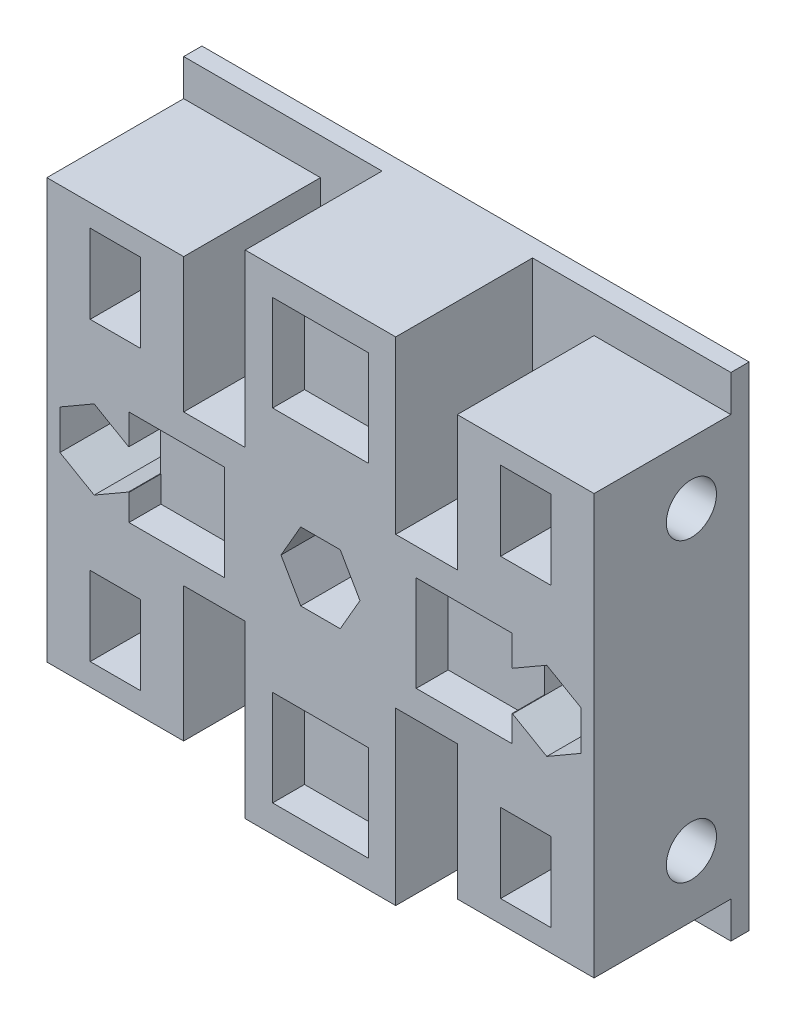
SolidWorks part; units mm, degrees
ref_plane "Plan de face" through (0, 0, 0) normal (0, 0, 1) x (1, 0, 0)
ref_plane "Plan de dessus" through (0, 0, 0) normal (0, 1, 0) x (1, 0, 0)
ref_plane "Plan de droite" through (0, 0, 0) normal (1, 0, 0) x (0, 0, -1)
sketch "Esquisse1" plane through (0, 0, 0) normal (0, 0, 1) x (1, 0, 0)
  line L1 (0, 0) -> (60, 0)
  line L2 (0, 0) -> (0, -54)
  line L3 (0, -54) -> (60, -54)
  line L4 (60, 0) -> (60, -54)
  circle A0 centre (5, -27) radius 2
  circle A1 centre (30, -27) radius 2
  circle A2 centre (55, -27) radius 2
  dimension "D1" = 4
  dimension "D2" = 4
  dimension "D3" = 4
  dimension "D4" = 25
  dimension "D5" = 25
  dimension "D6" = 60
  dimension "D7" = 54
  dimension "D8" = 27
  dimension "D9" = 5
  dimension "D10" = 27
  dimension "D11" = 27
extrude "Boss.-Extru.1" add sketch "Esquisse1" along normal blind 2
sketch "Esquisse2" plane through (0, 0, 2) normal (0, 0, 1) x (1, 0, 0)
  line L0 (0, 0) -> (0, -54) construction
  line L1 (0, -50) -> (15, -50)
  line L2 (15, -50) -> (15, -36.5)
  line L5 (0, -54) -> (60, -54) construction
  line L8 (15, -36.5) -> (0, -36.5)
  dimension "D1" = 4
  dimension "D2" = 15
  dimension "D4" = 13.5
extrude "Boss.-Extru.2" add sketch "Esquisse2" along normal blind 15
sketch "Esquisse4" plane through (0, 0, 0) normal (-1, 0, 0) x (0, 0, 1)
  line L1 (9.5, -45.4151) -> (9.5, -41.0849)
  line L2 (9.5, -41.0849) -> (5.75, -38.9199)
  line L3 (5.75, -38.9199) -> (2, -41.0849)
  line L4 (2, -41.0849) -> (2, -45.4151)
  line L5 (2, -45.4151) -> (5.75, -47.5801)
  line L6 (5.75, -47.5801) -> (9.5, -45.4151)
  line L7 (2, 0) -> (2, -36.5) construction
  line L8 (17, -36.5) -> (2, -36.5) construction
  circle A0 centre (5.75, -43.25) radius 3.75 construction
  dimension "D1" = 7.5
  dimension "D2" = 0
  dimension "D3" = 6.75
extrude "Enlèv. mat.-Extru.2" cut sketch "Esquisse4" against normal blind 16
sketch "Esquisse5" plane through (0, 0, 17) normal (0, 0, 1) x (1, 0, 0)
  line L0 (0, -50) -> (15, -50) construction
  line L1 (0, -36.5) -> (4.75, -36.5)
  line L2 (0, -36.5) -> (0, -50)
  line L3 (0, -50) -> (4.75, -50)
  line L4 (4.75, -36.5) -> (4.75, -50)
  line L5 (15, -36.5) -> (0, -36.5) construction
  line L6 (15, -50) -> (10.25, -50)
  line L7 (15, -50) -> (15, -36.5)
  line L8 (15, -36.5) -> (10.25, -36.5)
  line L9 (10.25, -50) -> (10.25, -36.5)
  dimension "D1" = 4.75
  dimension "D2" = 4.75
  dimension "D3" = 5.5
extrude "Boss.-Extru.3" add sketch "Esquisse5" against normal blind 17
sketch "Esquisse6" plane through (0, 0, 17) normal (0, 0, 1) x (1, 0, 0)
  line L0 (15, -36.5) -> (0, -36.5) construction
  line L1 (4.75, -36.5) -> (10.25, -36.5)
  line L2 (4.75, -36.5) -> (4.75, -50)
  line L3 (4.75, -50) -> (10.25, -50)
  line L4 (10.25, -36.5) -> (10.25, -50)
  line L5 (0, -50) -> (15, -50) construction
  line L6 (0, -36.5) -> (0, -50) construction
  line L7 (15, -50) -> (15, -36.5) construction
  line L9 (4.75, -38.92) -> (10.25, -38.92)
  line L10 (4.75, -38.92) -> (4.75, -47.58)
  line L11 (4.75, -47.58) -> (10.25, -47.58)
  line L12 (10.25, -38.92) -> (10.25, -47.58)
  dimension "D1" = 5.5
  dimension "D2" = 4.75
  dimension "D3" = 4.75
  dimension "D4" = 8.66
  dimension "D5" = 2.42
  dimension "D6" = 2.42
  dimension "D7" = 13.5
extrude "Enlèv. mat.-Extru.3" cut sketch "Esquisse6" against normal blind 11.25 contours L2 L11 L4 L9
sketch "Esquisse7" plane through (0, 0, 0) normal (-1, 0, 0) x (0, 0, 1)
  line L2 (17, -50) -> (2, -50) construction
  line L3 (2, -50) -> (2, -54) construction
  circle A0 centre (6.33, -43.25) radius 2.75
  dimension "D2" = 5.5
  dimension "D1" = 4.33
  dimension "D3" = 6.75
extrude "Enlèv. mat.-Extru.4" cut sketch "Esquisse7" against normal blind 28
ref_plane "Plan2" through (0, -27, 0) normal (0, -1, 0) x (-1, 0, 0)
ref_plane "Plan3" through (30, 0, 0) normal (-1, 0, 0) x (0, 0, 1)
mirror "Symétrie1" about plane through (0, -27, 0) normal (0, -1, 0) of "Enlèv. mat.-Extru.4", "Enlèv. mat.-Extru.3", "Boss.-Extru.3", "Enlèv. mat.-Extru.2", "Boss.-Extru.2"
mirror "Symétrie2" about plane through (30, 0, 0) normal (-1, 0, 0) of "Symétrie1", "Boss.-Extru.2", "Enlèv. mat.-Extru.2", "Boss.-Extru.3", "Enlèv. mat.-Extru.3", "Enlèv. mat.-Extru.4"
sketch "Esquisse8" plane through (0, 0, 2) normal (0, 0, 1) x (1, 0, 0)
  line L0 (0, -54) -> (60, -54) construction
  line L1 (35.25, -54) -> (24.75, -54)
  line L2 (35.25, -54) -> (35.25, -40.5)
  line L3 (35.25, -40.5) -> (24.75, -40.5)
  line L4 (24.75, -54) -> (24.75, -40.5)
  line L5 (35.25, -51) -> (24.75, -51)
  line L6 (38.25, -54) -> (21.75, -54)
  line L7 (38.25, -54) -> (38.25, -37.5)
  line L8 (38.25, -37.5) -> (21.75, -37.5)
  line L9 (21.75, -54) -> (21.75, -37.5)
  line L10 (30, 9.35) -> (30, -9.35) construction
  point P12 (30, -51)
  line M29 (0, -54) -> (60, -54)
  dimension "D1" = 3
  dimension "D2" = 10.5
  dimension "D3" = 10.5
  dimension "D4" = 3
  dimension "D5" = 3
  dimension "D6" = 0
  dimension "D7" = 3
extrude "Boss.-Extru.4" add sketch "Esquisse8" along normal blind 15 contours L9 L4 L3 L2 L7 L8 M29 | L2 L5 L4 M29
sketch "Esquisse12" plane through (0, 0, 2) normal (0, 0, 1) x (1, 0, 0)
  line L1 (15, -36.5) -> (0, -36.5)
  line L2 (15, -36.5) -> (15, -17.5)
  line L3 (15, -17.5) -> (0, -17.5)
  line L4 (0, -36.5) -> (0, -17.5)
extrude "Boss.-Extru.6" add sketch "Esquisse12" along normal blind 15
sketch "Esquisse9" plane through (0, 0, 2) normal (0, 0, 1) x (1, 0, 0)
  line L0 (-9.35, -27) -> (9.35, -27) construction
  line L1 (6, -18.75) -> (22.5, -18.75)
  line L2 (6, -18.75) -> (6, -35.25)
  line L3 (6, -35.25) -> (22.5, -35.25)
  line L4 (22.5, -18.75) -> (22.5, -35.25)
  line L5 (9, -21.75) -> (19.5, -21.75)
  line L6 (9, -21.75) -> (9, -32.25)
  line L7 (9, -32.25) -> (19.5, -32.25)
  line L8 (19.5, -21.75) -> (19.5, -32.25)
  line L10 (0, -4) -> (0, -50) construction
  point P8 (9, -27)
  dimension "D1" = 3
  dimension "D2" = 10.5
  dimension "D3" = 3
  dimension "D4" = 3
  dimension "D5" = 10.5
  dimension "D6" = 3
  dimension "D7" = 0
  dimension "D8" = 9
extrude "Boss.-Extru.7" add sketch "Esquisse9" along normal blind 15
sketch "Esquisse11" plane through (0, 0, 2) normal (0, 0, 1) x (1, 0, 0)
  line L1 (8.9358, -29.3869) -> (8.9358, -25.0568)
  line L2 (8.9358, -25.0568) -> (5.1858, -22.8918)
  line L3 (5.1858, -22.8918) -> (1.4358, -25.0568)
  line L4 (1.4358, -25.0568) -> (1.4358, -29.3869)
  line L5 (1.4358, -29.3869) -> (5.1858, -31.552)
  line L6 (5.1858, -31.552) -> (8.9358, -29.3869)
  line L7 (0, -4) -> (0, -50) construction
  circle A0 centre (5.1858, -27.2219) radius 3.75 construction
  dimension "D1" = 7.5
  dimension "D2" = 1.4358
extrude "Enlèv. mat.-Extru.6" cut sketch "Esquisse11" along normal blind 21
sketch "Esquisse13" plane through (0, 0, 2) normal (0, 0, 1) x (1, 0, 0)
  line L1 (19.5, -32.25) -> (9, -32.25)
  line L2 (19.5, -32.25) -> (19.5, -21.75)
  line L3 (19.5, -21.75) -> (9, -21.75)
  line L4 (9, -32.25) -> (9, -21.75)
  dimension "D1" = 10.5
  dimension "D2" = 10.5
extrude "Enlèv. mat.-Extru.7" cut sketch "Esquisse13" along normal blind 21
mirror "Symétrie3" about plane through (30, 0, 0) normal (-1, 0, 0) of "Boss.-Extru.6", "Enlèv. mat.-Extru.7", "Enlèv. mat.-Extru.6", "Boss.-Extru.7"
mirror "Symétrie4" about plane through (0, -27, 0) normal (0, -1, 0) of "Boss.-Extru.4"
sketch "Esquisse15" plane through (0, 0, 2) normal (0, 0, 1) x (1, 0, 0)
  line L0 (38.25, -37.5) -> (21.75, -37.5) construction
  line L1 (22.5, -37.5) -> (37.5, -37.5)
  line L2 (22.5, -37.5) -> (22.5, -16.5)
  line L3 (22.5, -16.5) -> (37.5, -16.5)
  line L4 (37.5, -37.5) -> (37.5, -16.5)
  line L7 (22.5, -35.25) -> (22.5, -18.75) construction
  line L8 (38.25, -16.5) -> (21.75, -16.5) construction
  line L10 (37.5, -35.25) -> (37.5, -18.75) construction
  line L11 (21.75, -37.5) -> (21.75, -35.25)
  line L12 (15, -35.25) -> (22.5, -35.25) construction
  line L13 (38.25, -37.5) -> (38.25, -35.25)
  line L14 (45, -35.25) -> (37.5, -35.25) construction
  line L15 (38.25, -16.5) -> (38.25, -18.75)
  line L16 (37.5, -18.75) -> (45, -18.75) construction
  line L17 (21.75, -16.5) -> (21.75, -18.75)
  line L18 (22.5, -18.75) -> (15, -18.75) construction
  point P8 (22.5, -27)
  point P9 (30, -16.5)
  point P12 (37.5, -27)
  circle M3 centre (30, -27) radius 2
  line M4 (38.25, -16.5) -> (21.75, -16.5)
  line M10 (15, -18.75) -> (22.5, -18.75)
  line M11 (22.5, -18.75) -> (22.5, -35.25)
  line M12 (22.5, -35.25) -> (15, -35.25)
  line M18 (21.75, -37.5) -> (38.25, -37.5)
  line M24 (45, -35.25) -> (37.5, -35.25)
  line M25 (37.5, -35.25) -> (37.5, -18.75)
  line M26 (37.5, -18.75) -> (45, -18.75)
  dimension "D1" = 0
  dimension "D2" = 0
  dimension "D3" = 0
extrude "Boss.-Extru.9" add sketch "Esquisse15" along normal blind 15 contours L4 L2 M18 M25 M4 M11 M3 | L11 L2 M18 M12 | L13 L4 M18 M24 | L15 L4 M4 M26 | L17 L2 M4 M10
sketch "Esquisse16" plane through (0, 0, 17) normal (0, 0, 1) x (1, 0, 0)
  line L0 (21.75, 0) -> (38.25, 0) construction
  line L1 (32.1651, -23.25) -> (27.8349, -23.25)
  line L2 (27.8349, -23.25) -> (25.6699, -27)
  line L3 (25.6699, -27) -> (27.8349, -30.75)
  line L4 (27.8349, -30.75) -> (32.1651, -30.75)
  line L5 (32.1651, -30.75) -> (34.3301, -27)
  line L6 (34.3301, -27) -> (32.1651, -23.25)
  circle A0 centre (30, -27) radius 3.75 construction
  dimension "D1" = 7.5
  dimension "D2" = 0
extrude "Enlèv. mat.-Extru.8" cut sketch "Esquisse16" against normal blind 10
sketch "Esquisse17" plane through (0, 0, 2) normal (0, 0, 1) x (1, 0, 0)
  line L1 (9, -21.75) -> (19.5, -21.75)
  line L2 (9, -21.75) -> (9, -32.25)
  line L3 (9, -32.25) -> (19.5, -32.25)
  line L4 (19.5, -21.75) -> (19.5, -32.25)
  line L5 (40.5, -21.75) -> (51, -21.75)
  line L6 (40.5, -21.75) -> (40.5, -32.25)
  line L7 (40.5, -32.25) -> (51, -32.25)
  line L8 (51, -21.75) -> (51, -32.25)
  line L9 (24.75, -3) -> (35.25, -3)
  line L10 (24.75, -3) -> (24.75, -13.5)
  line L11 (24.75, -13.5) -> (35.25, -13.5)
  line L12 (35.25, -3) -> (35.25, -13.5)
  line L13 (24.75, -40.5) -> (35.25, -40.5)
  line L14 (24.75, -40.5) -> (24.75, -51)
  line L15 (24.75, -51) -> (35.25, -51)
  line L16 (35.25, -40.5) -> (35.25, -51)
extrude "Boss.-Extru.10" add sketch "Esquisse17" along normal blind 11.5
sketch "Esquisse18" plane through (9, 0, 0) normal (1, 0, 0) x (0, 0, -1)
  line L0 (-17, -32.25) -> (-17, -21.75) construction
  line L1 (-17, -29.3869) -> (-13.5, -29.3869)
  line L2 (-17, -29.3869) -> (-17, -25.0568)
  line L3 (-17, -25.0568) -> (-13.5, -25.0568)
  line L4 (-13.5, -29.3869) -> (-13.5, -25.0568)
  line L5 (-13.5, -21.75) -> (-13.5, -32.25) construction
  dimension "D1" = 0
  dimension "D2" = 0
extrude "Enlèv. mat.-Extru.9" cut sketch "Esquisse18" against normal blind 1.5
mirror "Symétrie5" about plane through (30, 0, 0) normal (-1, 0, 0) of "Enlèv. mat.-Extru.9"
